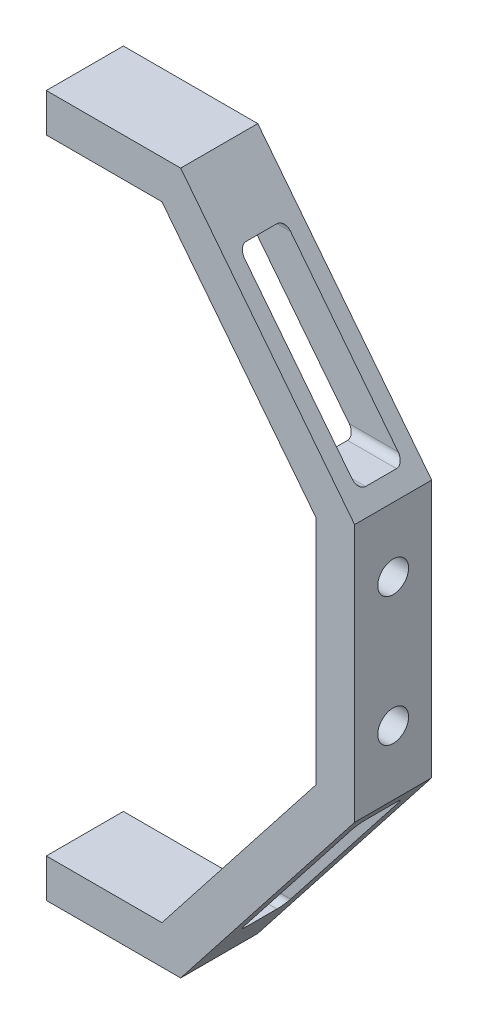
SolidWorks part; units mm, degrees
ref_plane "Front Plane" through (0, 0, 0) normal (0, 0, 1) x (1, 0, 0)
ref_plane "Top Plane" through (0, 0, 0) normal (0, 1, 0) x (1, 0, 0)
ref_plane "Right Plane" through (0, 0, 0) normal (1, 0, 0) x (0, 0, -1)
sketch "Sketch1" plane through (0, 0, 0) normal (0, 0, 1) x (1, 0, 0)
  line L0 (0, 172) -> (126.7138, 172) construction
  line L1 (0, 0) -> (121.7138, 0) construction
  line L2 (0, 177) -> (0, 167)
  line L3 (0, 167) -> (30, 167)
  line L4 (30, 167) -> (70, 116)
  line L5 (70, 116) -> (70, 56)
  line L6 (0, 172) -> (0, 0) construction
  line L7 (0, 86) -> (184.3995, 86) construction
  line L8 (0, 177) -> (34.8657, 177)
  line L9 (34.8657, 177) -> (80, 119.4538)
  line L10 (80, 119.4538) -> (80, 52.5462)
  line L11 (30, 5) -> (70, 56)
  line L12 (34.8657, -5) -> (80, 52.5462)
  line L13 (0, -5) -> (34.8657, -5)
  line L14 (0, -5) -> (0, 5)
  line L15 (0, 5) -> (30, 5)
  point P16 (80, 86)
  point P17 (70, 86)
  dimension "D1" = 172
  dimension "D2" = 70
  dimension "D3" = 5
  dimension "D4" = 5
  dimension "D5" = 10
  dimension "D6" = 10
  dimension "D7" = 30
  dimension "D8" = 60
extrude "Boss-Extrude1" add sketch "Sketch1" along normal blind 20
sketch "Sketch2" plane through (0, 0, 0) normal (-1, 0, 0) x (0, 0, 1)
  line L0 (0, 177) -> (20, 167) construction
  line L1 (0, 86) -> (20, 86) construction
  line L2 (0, 116) -> (0, 56) construction
  line L3 (20, 116) -> (20, 56) construction
  circle A0 centre (10, 172) radius 4
  circle A1 centre (10, 0) radius 4
  dimension "D1" = 8
extrude "Cut-Extrude1" cut sketch "Sketch2" against normal blind 30
sketch "Sketch3" plane through (80, 0, 0) normal (1, 0, 0) x (0, 0, -1)
  line L0 (-10, 119.4538) -> (-10, 52.5462) construction
  line L1 (-20, 119.4538) -> (0, 119.4538) construction
  line L2 (-20, 52.5462) -> (0, 52.5462) construction
  line L3 (-20, 86) -> (0, 86) construction
  line L4 (-20, 52.5462) -> (-20, 119.4538) construction
  line L5 (0, 52.5462) -> (0, 119.4538) construction
  line L6 (-20, 119.4538) -> (0, 86) construction
  line L7 (0, 86) -> (-20, 52.5462) construction
  circle A0 centre (-10, 102.7269) radius 4
  circle A1 centre (-10, 69.2731) radius 4
  dimension "D1" = 8
  dimension "D2" = 8
extrude "Cut-Extrude2" cut sketch "Sketch3" against normal blind 30
sketch "Sketch4" plane through (80, 0, 0) normal (1, 0, 0) x (0, 0, -1)
  line L0 (-20, 119.4538) -> (-20, 177) construction
  line L1 (-14, 163) -> (-6, 163)
  line L2 (-16, 161) -> (-16, 125.4538)
  line L3 (-14, 123.4538) -> (-6, 123.4538)
  line L4 (-4, 161) -> (-4, 125.4538)
  line L5 (0, 119.4538) -> (0, 177) construction
  line L6 (-20, 119.4538) -> (0, 119.4538) construction
  line L7 (-20, 167) -> (0, 167) construction
  line L8 (-20, 86) -> (0, 86) construction
  line L9 (-20, 52.5462) -> (-20, 119.4538) construction
  line L10 (0, 52.5462) -> (0, 119.4538) construction
  line L11 (-14, 48.5462) -> (-6, 48.5462)
  line L12 (-4, 11) -> (-4, 46.5462)
  line L13 (-14, 9) -> (-6, 9)
  line L14 (-16, 11) -> (-16, 46.5462)
  arc A0 (-16, 125.4538) -> (-14, 123.4538) centre (-14, 125.4538) ccw
  arc A1 (-6, 123.4538) -> (-4, 125.4538) centre (-6, 125.4538) ccw
  arc A2 (-6, 163) -> (-4, 161) centre (-6, 161) cw
  arc A3 (-14, 163) -> (-16, 161) centre (-14, 161) ccw
  arc A4 (-6, 48.5462) -> (-4, 46.5462) centre (-6, 46.5462) cw
  arc A5 (-6, 9) -> (-4, 11) centre (-6, 11) ccw
  arc A6 (-16, 46.5462) -> (-14, 48.5462) centre (-14, 46.5462) cw
  arc A7 (-14, 9) -> (-16, 11) centre (-14, 11) cw
  dimension "D5" = 2
  dimension "D1" = 4
  dimension "D2" = 4
  dimension "D3" = 4
  dimension "D4" = 4
extrude "Cut-Extrude3" cut sketch "Sketch4" against normal blind 87
